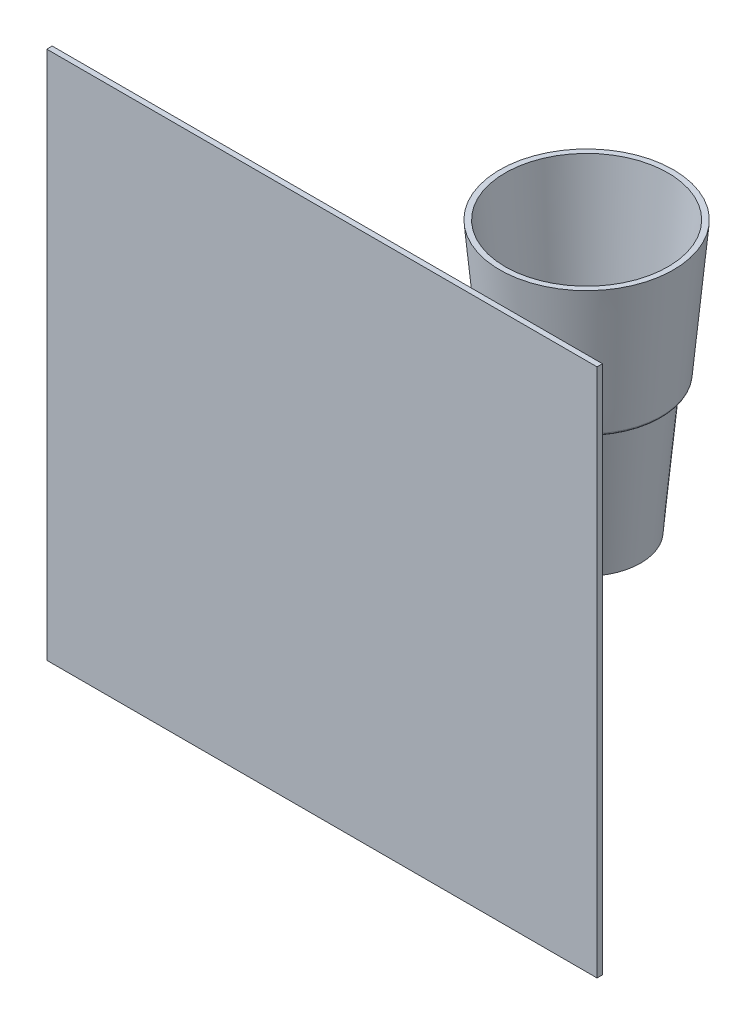
SolidWorks part; units mm, degrees
ref_plane "Front Plane" through (0, 0, 0) normal (0, 0, 1) x (1, 0, 0)
ref_plane "Top Plane" through (0, 0, 0) normal (0, 1, 0) x (1, 0, 0)
ref_plane "Right Plane" through (0, 0, 0) normal (1, 0, 0) x (0, 0, -1)
sketch "Sketch1" plane through (0, 0, 0) normal (0, 0, 1) x (1, 0, 0)
  line L0 (0, 0) -> (25.4, 0)
  line L1 (25.4, 0) -> (31.1859, 63.5)
  line L2 (31.1859, 63.5) -> (34.9959, 63.5)
  line L3 (34.9959, 63.5) -> (40.7818, 127)
  line L4 (40.7818, 127) -> (0, 127)
  line L6 (0, 0) -> (0, 127)
  dimension "D1" = 25.4
  dimension "D2" = 63.5
  dimension "D3" = 63.5
  dimension "D4" = 3.81
revolve "Revolve2" add sketch "Sketch1" angle 360 about L6
fillet "Fillet1" radius 1.27 2 edges at (0, 63.5, -34.9959) (0, 63.5, -31.1859)
shell "Shell1" thickness 2.54
ref_plane "Plane1" through (0, 0, 127) normal (0, 0, 1) x (1, 0, 0)
sketch "Sketch2" plane through (0, 0, 127) normal (0, 0, 1) x (1, 0, 0)
  line L1 (-124.0794, 199.1733) -> (134.4399, 199.1733)
  line L2 (-124.0794, 199.1733) -> (-124.0794, -49.4789)
  line L3 (-124.0794, -49.4789) -> (134.4399, -49.4789)
  line L4 (134.4399, 199.1733) -> (134.4399, -49.4789)
extrude "Boss-Extrude1" add sketch "Sketch2" along normal blind 2.54 separate body
